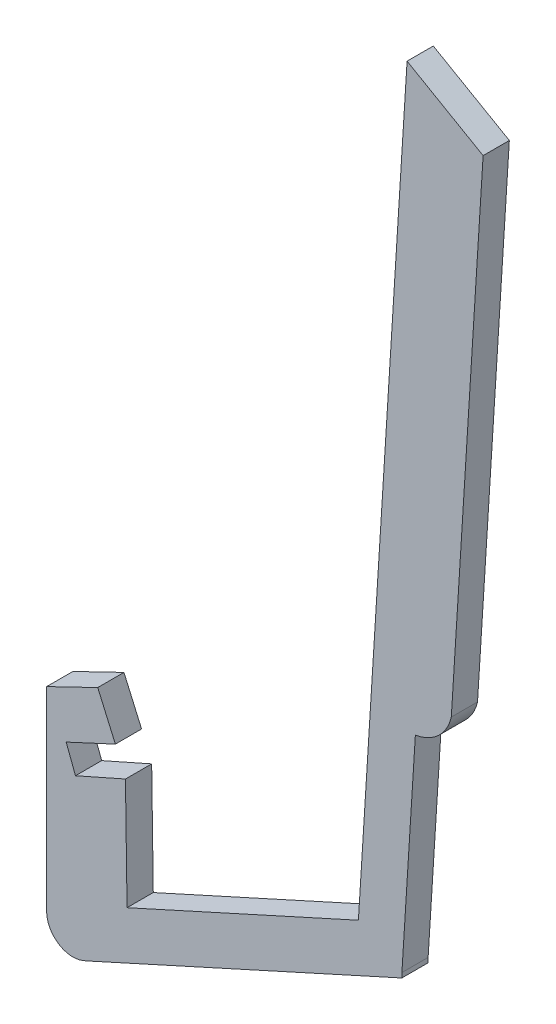
SolidWorks part; units mm, degrees
ref_plane "Front" through (0, 0, 0) normal (0, 0, 1) x (1, 0, 0)
ref_plane "Top" through (0, 0, 0) normal (0, 1, 0) x (1, 0, 0)
ref_plane "Right" through (0, 0, 0) normal (1, 0, 0) x (0, 0, -1)
sketch "Sketch1" plane through (0, 0, 0) normal (0, 0, 1) x (1, 0, 0)
  line L0 (827.974, -43.2458) -> (829.5144, -18.9379)
  line L2 (833.6266, -15.1004) -> (837.2677, 42.3561)
  line L3 (787.3269, -35.2304) -> (787.3269, -57.5267)
  line L5 (837.2677, 42.3561) -> (828.5672, 47.3669)
  line L6 (828.5672, 47.3669) -> (822.996, -40.5471)
  line L37 (792.0334, -60.0672) -> (827.9683, -43.7861)
  line L45 (822.996, -40.5471) -> (796.5255, -52.5401)
  line L46 (796.5255, -52.5401) -> (796.3425, -39.881)
  line L47 (796.3425, -39.881) -> (790.6246, -42.4157)
  line L48 (790.6246, -42.4157) -> (789.5603, -39.6109)
  line L49 (789.5603, -39.6109) -> (795.1881, -37.0024)
  line L50 (795.1881, -37.0024) -> (793.1717, -32.402)
  line L51 (793.1717, -32.402) -> (787.3269, -35.2304)
  arc A0 (792.0334, -60.0672) -> (791.3642, -60.3417) centre (787.9065, -50.9585) cw
  arc A1 (791.3642, -60.3417) -> (787.3269, -57.5267) centre (790.3269, -57.5267) cw
  arc A2 (827.9683, -43.7861) -> (827.974, -43.2458) centre (817.9753, -43.4105) ccw
  arc A4 (833.6266, -15.1004) -> (829.5144, -18.9379) centre (828.7545, -14.0015) cw
  dimension "D2" = 118
  dimension "D3" = 3
  dimension "D1" = 10
  dimension "D4" = 9
extrude "Base-Extrude" add sketch "Sketch1" along normal blind 3
